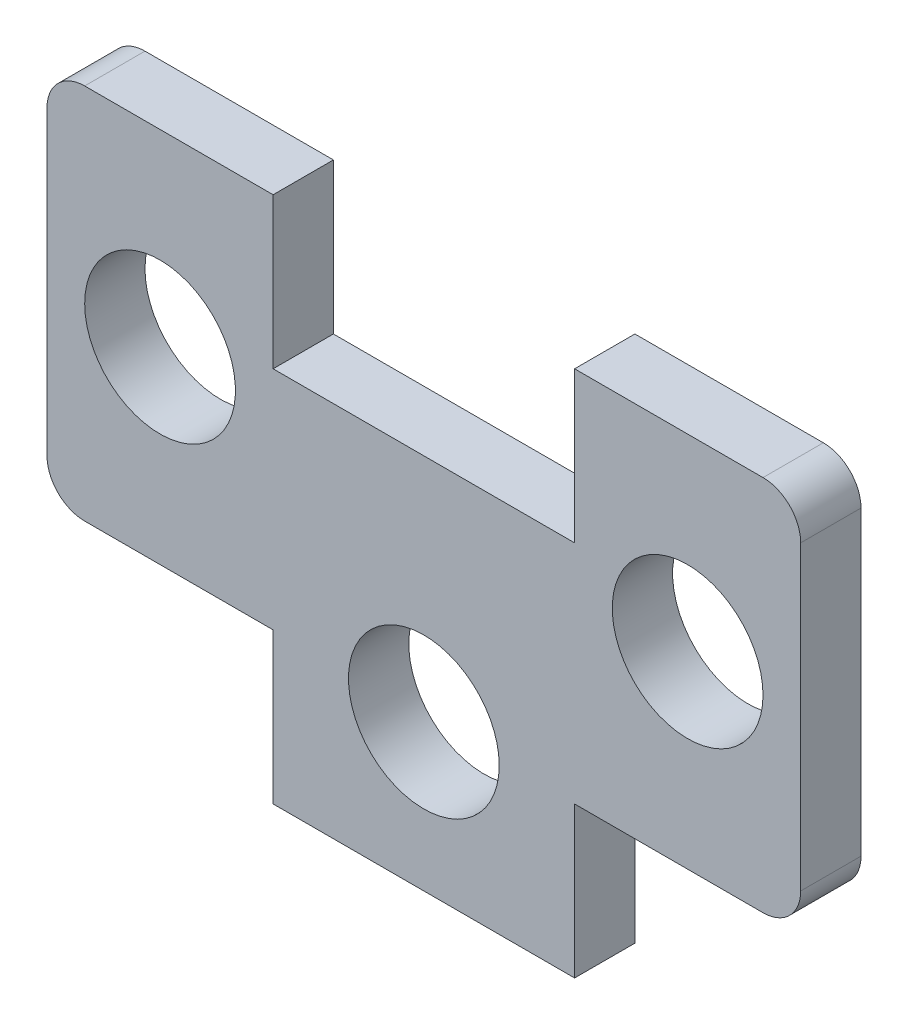
SolidWorks part; units mm, degrees
ref_plane "Front Plane" through (0, 0, 0) normal (0, 0, 1) x (1, 0, 0)
ref_plane "Top Plane" through (0, 0, 0) normal (0, 1, 0) x (1, 0, 0)
ref_plane "Right Plane" through (0, 0, 0) normal (1, 0, 0) x (0, 0, -1)
sketch "Sketch1" plane through (0, 0, 0) normal (0, 0, 1) x (1, 0, 0)
  line L0 (-100, -122.0945) -> (-100, -222.0945)
  line L1 (-225, -122.0945) -> (-100, -122.0945)
  line L2 (-250, -97.0945) -> (-250, 102.9055)
  line L3 (-225, 127.9055) -> (-100, 127.9055)
  line L4 (250, -97.0945) -> (250, 102.9055)
  line L5 (-100, 127.9055) -> (-100, 27.9055)
  line L6 (-100, 27.9055) -> (100, 27.9055)
  line L7 (-100, -222.0945) -> (100, -222.0945)
  line L8 (100, -222.0945) -> (100, -122.0945)
  line L9 (100, 27.9055) -> (100, 127.9055)
  line L10 (100, 127.9055) -> (225, 127.9055)
  line L11 (0, -530.2047) -> (0, 387.7903) construction
  line L12 (100, -122.0945) -> (225, -122.0945)
  circle A0 centre (0, -125) radius 50
  circle A1 centre (175, 2.9055) radius 50
  circle A2 centre (-175, 2.9055) radius 50
  arc A3 (250, -97.0945) -> (225, -122.0945) centre (225, -97.0945) cw
  arc A4 (-225, -122.0945) -> (-250, -97.0945) centre (-225, -97.0945) cw
  arc A5 (-250, 102.9055) -> (-225, 127.9055) centre (-225, 102.9055) cw
  arc A6 (250, 102.9055) -> (225, 127.9055) centre (225, 102.9055) ccw
  point P0 (0, 0)
  point P24 (250, -122.0945)
  point P29 (-250, 127.9055)
  point P32 (250, 127.9055)
  dimension "D7" = 100
  dimension "D5" = 25
  dimension "D1" = 500
  dimension "D2" = 250
  dimension "D3" = 100
  dimension "D4" = 200
  dimension "D6" = 200
  dimension "D8" = 75
  dimension "D9" = 125
  dimension "D10" = 100
extrude "Boss-Extrude1" add sketch "Sketch1" along normal blind 40
